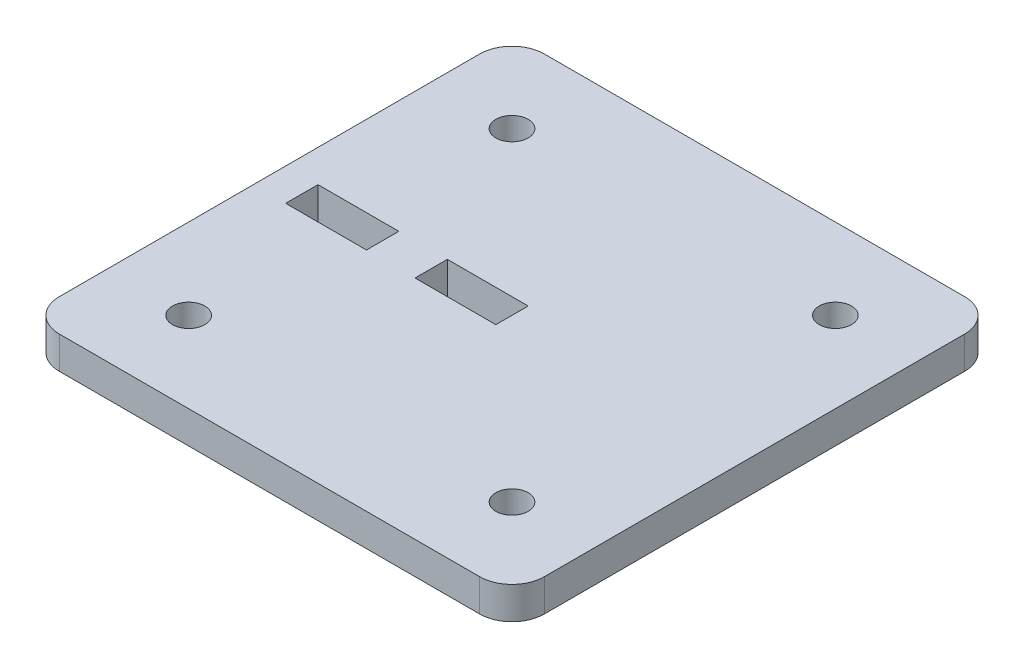
SolidWorks part; units mm, degrees
material "Acrylic (Medium-high impact)"
ref_plane "Front Plane" through (0, 0, 0) normal (0, 0, 1) x (1, 0, 0)
ref_plane "Top Plane" through (0, 0, 0) normal (0, 1, 0) x (1, 0, 0)
ref_plane "Right Plane" through (0, 0, 0) normal (1, 0, 0) x (0, 0, -1)
sketch "Sketch1" plane through (0, 0, 0) normal (0, 1, 0) x (1, 0, 0)
  line L1 (15, -15) -> (-15, -15)
  line L2 (15, -15) -> (15, 15)
  line L3 (15, 15) -> (-15, 15)
  line L4 (-15, -15) -> (-15, 15)
  line L5 (15, -15) -> (-15, 15) construction
  line L6 (15, 15) -> (-15, -15) construction
  point P0 (0, 0)
  dimension "D1" = 30
  dimension "D2" = 30
extrude "Boss-Extrude1" add sketch "Sketch1" along normal blind 2
sketch "Sketch2" plane through (0, 2, 0) normal (0, 1, 0) x (1, 0, 0)
  line L0 (15, 15) -> (-15, 15) construction
  line L1 (0, -1) -> (-5, -1)
  line L2 (0, -1) -> (0, 1)
  line L3 (0, 1) -> (-5, 1)
  line L4 (-5, -1) -> (-5, 1)
  line L5 (15, -15) -> (15, 15) construction
  line L6 (-8, 1) -> (-13, 1)
  line L7 (-8, 1) -> (-8, -1)
  line L8 (-8, -1) -> (-13, -1)
  line L9 (-13, 1) -> (-13, -1)
  line L10 (0, 15) -> (0, -15) construction
  line L11 (-15, -15) -> (15, -15) construction
  line L12 (15, 0) -> (-15, 0) construction
  line L13 (-15, 15) -> (-15, -15) construction
  circle A0 centre (10, 10) radius 1
  circle A1 centre (10, -10) radius 1
  circle A2 centre (-10, -10) radius 1
  circle A3 centre (-10, 10) radius 1
  dimension "D9" = 2
  dimension "D1" = 2
  dimension "D2" = 5
  dimension "D3" = 0
  dimension "D4" = 14
  dimension "D5" = 2
  dimension "D6" = 5
  dimension "D7" = 14
  dimension "D8" = 3
  dimension "D10" = 5
  dimension "D11" = 5
extrude "Cut-Extrude1" cut sketch "Sketch2" against normal blind 2
fillet "Fillet2" radius 2 4 edges at (-15, 1, -15) (15, 1, -15) (15, 1, 15) (-15, 1, 15)
